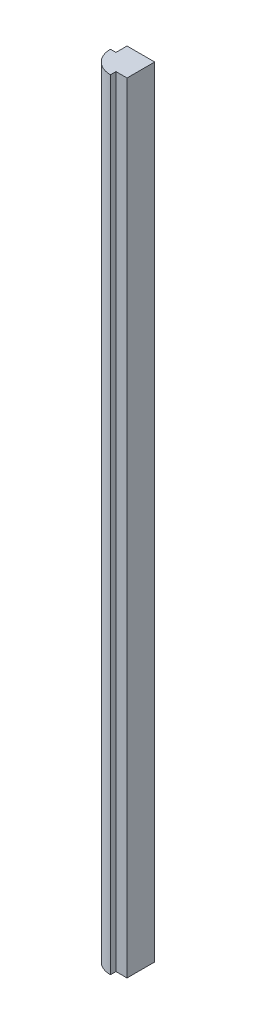
SolidWorks part; units mm, degrees
material "Free-Cutting Brass, UNS C36000"
ref_plane "Front Plane" through (0, 0, 0) normal (0, 0, 1) x (1, 0, 0)
ref_plane "Top Plane" through (0, 0, 0) normal (0, 1, 0) x (1, 0, 0)
ref_plane "Right Plane" through (0, 0, 0) normal (1, 0, 0) x (0, 0, -1)
sketch "Sketch1" plane through (0, 0, 0) normal (0, 1, 0) x (1, 0, 0)
  line L1 (12.7, 0) -> (19.05, 0)
  line L2 (0, 12.7) -> (0, 19.05)
  line L3 (0, 19.05) -> (19.05, 19.05)
  line L4 (19.05, 0) -> (19.05, 19.05)
  line L5 (12.7, 0) -> (19.05, 0)
  line L6 (12.7, 0) -> (12.7, 3.175)
  line L7 (12.7, 3.175) -> (19.05, 3.175)
  line L8 (19.05, 0) -> (19.05, 3.175)
  line L9 (0, 12.7) -> (3.175, 12.7)
  line L10 (0, 12.7) -> (0, 19.05)
  line L11 (0, 19.05) -> (3.175, 19.05)
  line L12 (3.175, 12.7) -> (3.175, 19.05)
  arc A0 (0, 12.7) -> (12.7, 0) centre (12.7, 12.7) ccw
  point P7 (0, 0)
  dimension "D3" = 12.7
  dimension "D1" = 19.05
  dimension "D2" = 19.05
  dimension "D4" = 3.175
  dimension "D5" = 3.175
extrude "Boss-Extrude1" add sketch "Sketch1" along normal blind 447.04 contours L9 A0 L6 L7 L4 L3 L12
